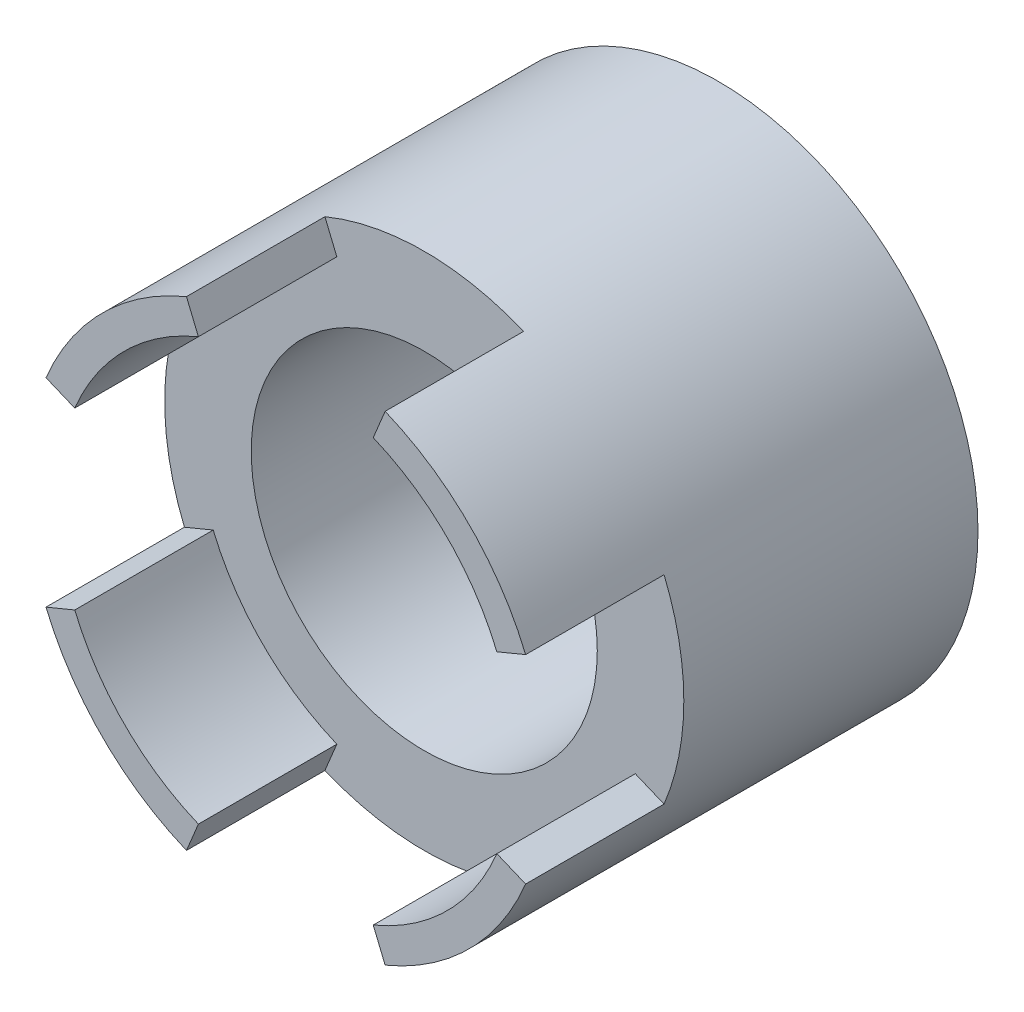
SolidWorks part; units mm, degrees
ref_plane "Front Plane" through (0, 0, 0) normal (0, 0, 1) x (1, 0, 0)
ref_plane "Top Plane" through (0, 0, 0) normal (0, 1, 0) x (1, 0, 0)
ref_plane "Right Plane" through (0, 0, 0) normal (1, 0, 0) x (0, 0, -1)
sketch "Sketch1" plane through (0, 0, 0) normal (0, 0, 1) x (1, 0, 0)
  circle A0 centre (0, 0) radius 19.05
  circle A1 centre (0, 0) radius 16.764
  circle A3 centre (0, 0) radius 12.7
  dimension "D1" = 38.1
  dimension "D2" = 25.4
  dimension "D3" = 2.286
extrude "Boss-Extrude1" add sketch "Sketch1" against normal blind 31.75 contours A0 A1
sketch "Sketch2" plane through (0, 0, 0) normal (0, 0, 1) x (1, 0, 0)
  circle A0 centre (0, 0) radius 16.764
  circle A1 centre (0, 0) radius 12.7
  circle A2 centre (0, 0) radius 16.764 construction
  dimension "D1" = 25.4
extrude "Boss-Extrude2" add sketch "Sketch2" along a picked direction on the side against the normal blind 20.32 from offset 10.16 offset against normal yes
sketch "Sketch4" plane through (0, 0, 0) normal (0, 0, 1) x (1, 0, 0)
  line L0 (0, 0) -> (0, 19.05) construction
  line L1 (0, 0) -> (-7.2901, 17.5999) construction
  line L2 (0, 0) -> (7.2901, 17.5999) construction
  line L3 (-7.2901, 17.5999) -> (-6.4153, 15.4879)
  line L4 (7.2901, 17.5999) -> (6.4153, 15.4879)
  line L5 (17.5999, -7.2901) -> (15.4879, -6.4153)
  line L6 (17.5999, 7.2901) -> (15.4879, 6.4153)
  line L7 (-7.2901, -17.5999) -> (-6.4153, -15.4879)
  line L8 (7.2901, -17.5999) -> (6.4153, -15.4879)
  line L9 (-17.5999, 7.2901) -> (-15.4879, 6.4153)
  line L10 (-17.5999, -7.2901) -> (-15.4879, -6.4153)
  circle A0 centre (0, 0) radius 19.05 construction
  arc A1 (-6.4153, 15.4879) -> (6.4153, 15.4879) centre (0, 0) cw
  arc A2 (-7.2901, 17.5999) -> (7.2901, 17.5999) centre (0, 0) cw
  arc A3 (15.4879, 6.4153) -> (15.4879, -6.4153) centre (0, 0) cw
  circle A4 centre (0, 0) radius 16.764 construction
  arc A5 (17.5999, 7.2901) -> (17.5999, -7.2901) centre (0, 0) cw
  arc A6 (6.4153, -15.4879) -> (-6.4153, -15.4879) centre (0, 0) cw
  arc A7 (7.2901, -17.5999) -> (-7.2901, -17.5999) centre (0, 0) cw
  arc A8 (-15.4879, -6.4153) -> (-15.4879, 6.4153) centre (0, 0) cw
  arc A9 (-17.5999, -7.2901) -> (-17.5999, 7.2901) centre (0, 0) cw
  point P27 (0, 0)
  dimension "D1" = 45
  dimension "D2" = 22.5
  dimension "D3" = 4
extrude "Cut-Extrude1" cut sketch "Sketch4" against normal blind 10.16
